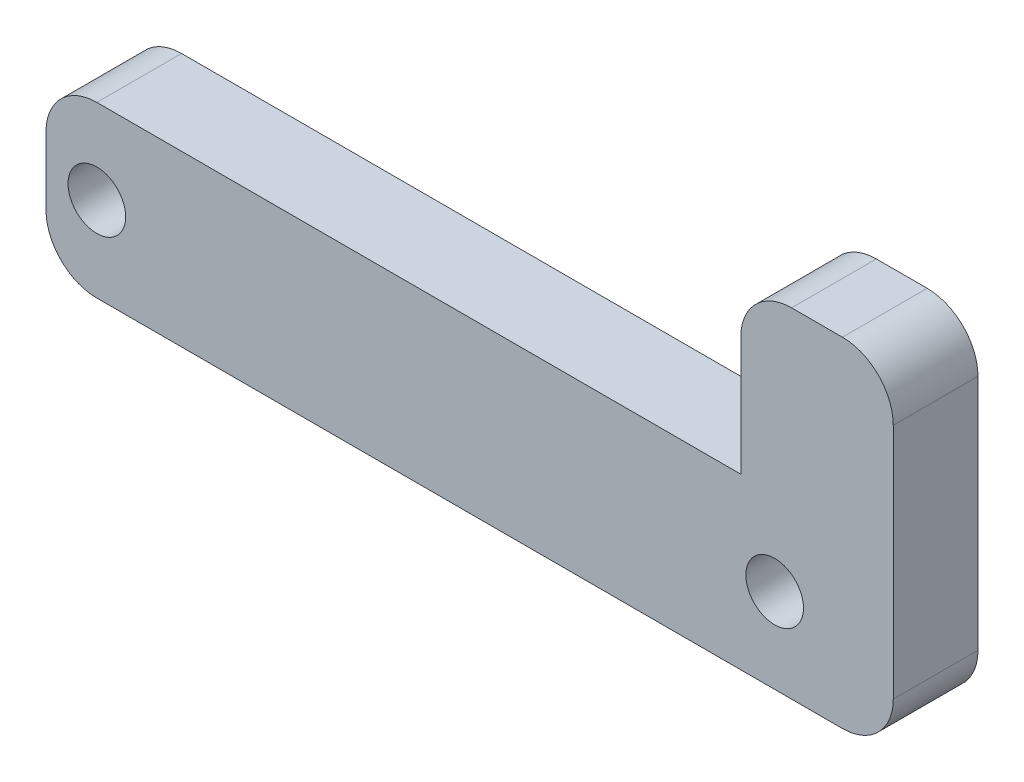
SolidWorks part; units mm, degrees
ref_plane "前视基准面" through (0, 0, 0) normal (0, 0, 1) x (1, 0, 0)
ref_plane "上视基准面" through (0, 0, 0) normal (0, 1, 0) x (1, 0, 0)
ref_plane "右视基准面" through (0, 0, 0) normal (1, 0, 0) x (0, 0, -1)
sketch "草图1" plane through (0, 0, 0) normal (0, 0, 1) x (1, 0, 0)
  line L0 (0, 5) -> (46, 5) construction
  line L1 (0, 0) -> (46, 0)
  line L2 (0, 0) -> (0, 20)
  line L3 (0, 20) -> (46, 20)
  line L4 (46, 0) -> (46, 20)
  line L5 (23, 0) -> (23, 20) construction
  circle A0 centre (3, 5) radius 1.7
  circle A1 centre (43, 5) radius 1.7
  dimension "D4" = 3.4
  dimension "D5" = 40
  dimension "D1" = 46
  dimension "D2" = 20
  dimension "D3" = 5
extrude "凸台-拉伸1" add sketch "草图1" against normal blind 5
sketch "草图3" plane through (0, 0, 0) normal (0, 0, 1) x (1, 0, 0)
  line L0 (0, 10) -> (41, 10)
  line L1 (0, 20) -> (0, 0) construction
  line L2 (41, 10) -> (41, 20)
  line L3 (46, 20) -> (0, 20) construction
  line L4 (46, 0) -> (46, 20) construction
  line L9 (0, 20) -> (0, 0)
  line L10 (0, 0) -> (46, 0)
  line L11 (46, 0) -> (46, 20)
  line L12 (46, 20) -> (0, 20)
  line L13 (0, 20) -> (0, 10)
  line L16 (46, 20) -> (0, 20)
  line M8 (0, 20) -> (0, 0)
  line M11 (46, 20) -> (0, 20)
  dimension "D1" = 5
  dimension "D2" = 0
extrude "切除-拉伸1" cut sketch "草图3" against normal blind 5 contours L0 L2 M11 M8
fillet "圆角1" radius 3 2 edges at (0, 10, -2.5) (41, 20, -2.5)
sketch "草图4" plane through (0, 0, 0) normal (0, 0, 1) x (1, 0, 0)
  line L0 (46, 20) -> (44, 20) construction
  line L1 (46, 0) -> (50, 0)
  line L2 (46, 0) -> (46, 20)
  line L3 (46, 20) -> (50, 20)
  line L4 (50, 0) -> (50, 20)
  dimension "D1" = 4
extrude "凸台-拉伸2" add sketch "草图4" against normal blind 5
fillet "圆角2" radius 3 2 edges at (50, 0, -2.5) (50, 20, -2.5)
fillet "圆角3" radius 3 1 edges at (0, 0, -2.5)
